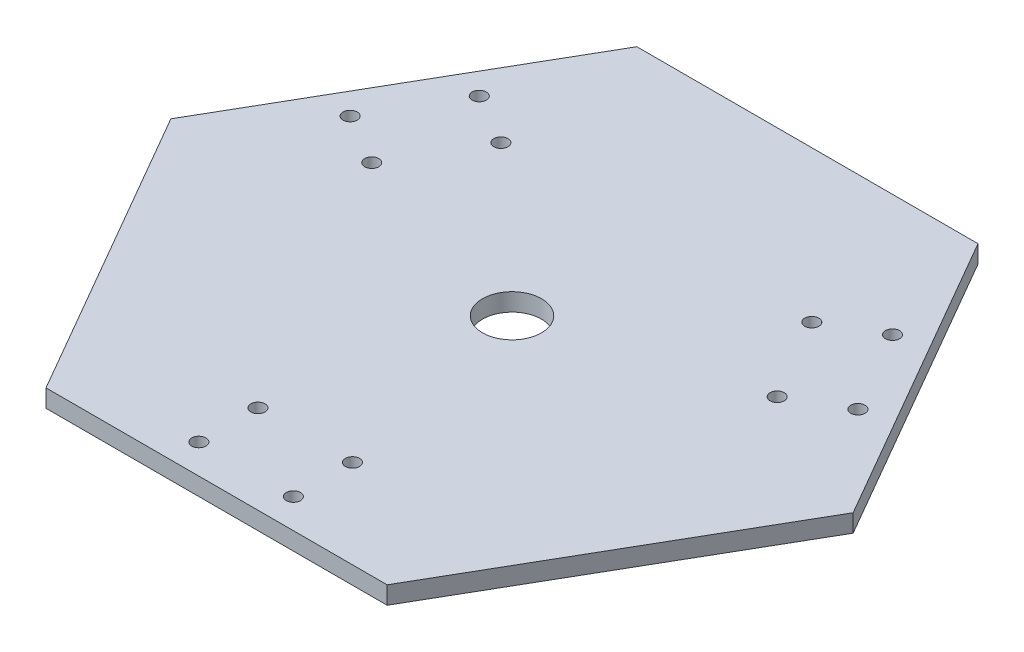
SolidWorks part; units mm, degrees
ref_plane "前视基准面" through (0, 0, 0) normal (0, 0, 1) x (1, 0, 0)
ref_plane "上视基准面" through (0, 0, 0) normal (0, 1, 0) x (1, 0, 0)
ref_plane "右视基准面" through (0, 0, 0) normal (1, 0, 0) x (0, 0, -1)
other "Configuration Table"
sketch "草图1" plane through (0, 0, 0) normal (0, 1, 0) x (1, 0, 0)
  line L1 (28.8675, 50) -> (-28.8675, 50)
  line L2 (-28.8675, 50) -> (-57.735, 0)
  line L3 (-57.735, 0) -> (-28.8675, -50)
  line L4 (-28.8675, -50) -> (28.8675, -50)
  line L5 (28.8675, -50) -> (57.735, 0)
  line L6 (57.735, 0) -> (28.8675, 50)
  circle A0 centre (0, 0) radius 50 construction
  dimension "D1" = 100
extrude "凸台-拉伸1" add sketch "草图1" along normal blind 3
sketch "草图2" plane through (0, 3, 0) normal (0, 1, 0) x (1, 0, 0)
  circle A0 centre (0, 0) radius 5
  dimension "D1" = 10
extrude "切除-拉伸1" cut sketch "草图2" against normal blind 3
sketch "草图3" plane through (0, 0, 0) normal (0, -1, 0) x (1, 0, 0)
  line L0 (0, 40) -> (0, 0) construction
  line L1 (-8, 35) -> (8, 35) construction
  line L2 (-8, 35) -> (-8, 45) construction
  line L3 (-8, 45) -> (8, 45) construction
  line L4 (8, 35) -> (8, 45) construction
  line L5 (-8, 35) -> (8, 45) construction
  line L6 (-8, 45) -> (8, 35) construction
  line L7 (-28.8675, 50) -> (28.8675, 50) construction
  circle A0 centre (-8, 45) radius 1.2
  circle A1 centre (8, 45) radius 1.2
  circle A2 centre (8, 35) radius 1.2
  circle A3 centre (-8, 35) radius 1.2
  point P0 (0, 40)
  dimension "D4" = 2.4
  dimension "D5" = 2.4
  dimension "D6" = 2.4
  dimension "D7" = 2.4
  dimension "D1" = 10
  dimension "D2" = 16
  dimension "D3" = 10
extrude "切除-拉伸2" cut sketch "草图3" against normal blind 3
pattern_circular "阵列(圆周)1" count 3 over 360 about axis through (0, 0, 0) along (0, 1, 0) of "切除-拉伸2"
